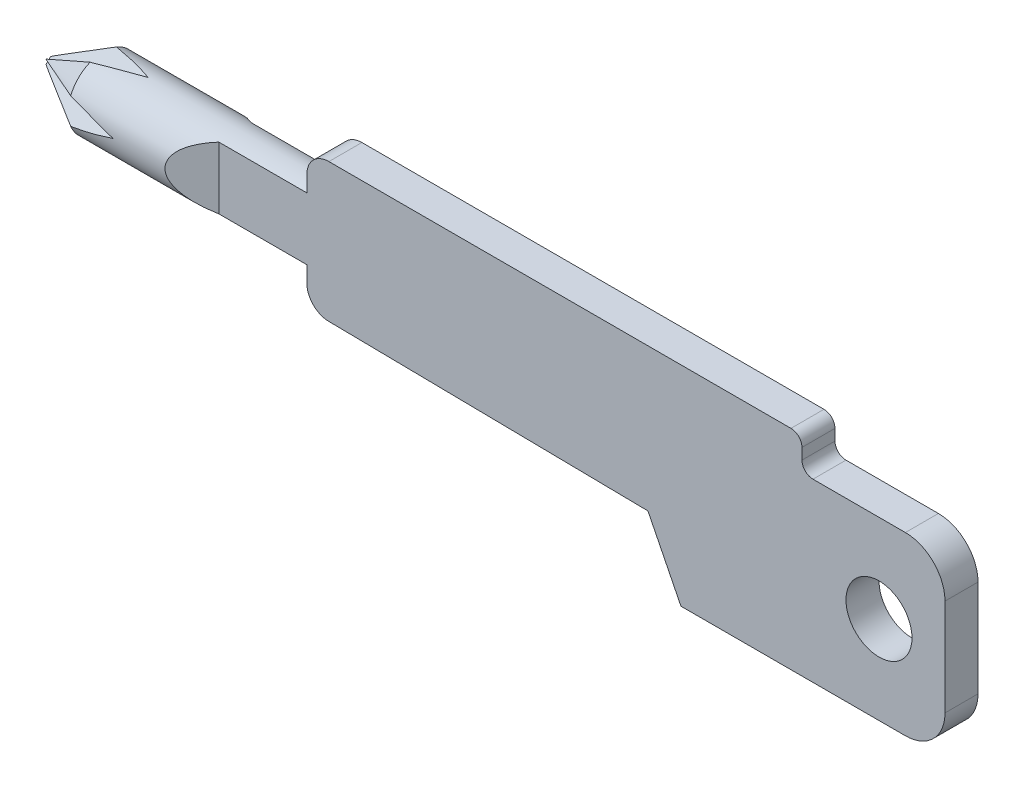
SolidWorks part; units mm, degrees
ref_plane "Front Plane" through (0, 0, 0) normal (0, 0, 1) x (1, 0, 0)
ref_plane "Top Plane" through (0, 0, 0) normal (0, 1, 0) x (1, 0, 0)
ref_plane "Right Plane" through (0, 0, 0) normal (1, 0, 0) x (0, 0, -1)
sketch "Sketch1" plane through (0, 0, 0) normal (0, 0, 1) x (1, 0, 0)
  line L2 (1, 9.5) -> (22, 9.5)
  line L3 (22.5, 9) -> (22.5, 8.5)
  line L4 (23, 8) -> (29, 8)
  line L5 (29, 8) -> (29, 0)
  line L6 (29, 0) -> (17, 0)
  line L21 (17, 0) -> (15.5, 3)
  line L22 (15.5, 3) -> (1, 3.2071)
  line L25 (0, 6.3536) -> (0, 8.5)
  line L26 (0, 6.3536) -> (0, 4.2071)
  arc A2 (23, 8) -> (22.5, 8.5) centre (23, 8.5) cw
  arc A3 (22.5, 9) -> (22, 9.5) centre (22, 9) ccw
  circle A6 centre (26, 4) radius 1.5
  arc A17 (0, 4.2071) -> (1, 3.2071) centre (1, 4.2071) ccw
  arc A18 (0, 8.5) -> (1, 9.5) centre (1, 8.5) cw
  point P3 (0, 0)
  point P15 (26, 8)
  point P18 (22.5, 8)
  point P22 (22.5, 9.5)
  point P24 (9.5435, 3.8604)
  point P27 (6.0812, 4.067)
  point P28 (0.2929, 3.5)
  point P29 (17.1415, 3)
  point P30 (0, 0)
  point P31 (0, 0)
  point P32 (13.8071, 3)
  point P33 (13.8626, 3)
  point P34 (14.3287, 3)
  point P35 (14.3287, 3)
  point P36 (0, 0)
  point P37 (0, 4.859)
  point P38 (16.1094, 3.2071)
  dimension "D12" = 1
  dimension "D13" = 0.5
  dimension "D7" = 12
  dimension "D8" = 4
  dimension "D2" = 3
  dimension "D9" = 6.5
  dimension "D14" = 7
  dimension "D3" = 1.5
  dimension "D4" = 26
  dimension "D5" = 8
  dimension "D6" = 6.5
  dimension "D10" = 6
extrude "Boss-Extrude1" add sketch "Sketch1" along normal mid plane 1.5
fillet "Fillet1" radius 1.8 2 edges at (29, 0, 0) (29, 8, 0)
sketch "Sketch2" plane through (0, 0, 0) normal (0, 0, 1) x (1, 0, 0)
  line L1 (0, 4.2071) -> (0, 8.5) construction
  line L2 (0, 7.9536) -> (0, 6.3536)
  line L3 (0, 6.3536) -> (-12.5, 6.3536)
  line L4 (-10, 7.9536) -> (0, 7.9536)
  line L5 (0, 4.2071) -> (0, 8.5) construction
  line L6 (-12.5, 6.3536) -> (-12.5, 6.5036)
  line L7 (-12.5, 6.5036) -> (-10, 7.9536)
  point P10 (0, 6.3536)
  dimension "D1" = 2.5
  dimension "D2" = 12.5
  dimension "D3" = 1.6
  dimension "D4" = 0.15
revolve "Revolve1" add sketch "Sketch2" angle 360 about L3
sketch "Sketch3" plane through (0, 0, 0) normal (0, 0, 1) x (1, 0, 0)
  line L0 (-12.5, 6.5036) -> (-10, 6.7036)
  line L1 (-10, 7.9536) -> (-10, 4.7536) construction
  line L2 (-10, 6.7036) -> (-8.5, 6.3536)
  line L3 (-8.5, 6.3536) -> (-10, 6.0036)
  line L4 (-10, 6.0036) -> (-12.5, 6.2036)
  line L5 (-12.5, 6.3536) -> (-7.5832, 6.3536) construction
  line L6 (-12.5, 6.5036) -> (-12.5, 6.2036) construction
  line L7 (0, 7.9536) -> (-10, 7.9536) construction
  line L8 (-12.5, 6.5036) -> (-12.5, 6.2036)
  dimension "D1" = 1.25
  dimension "D2" = 4
ref_plane "Plane2" through (0, 0, 1.75) normal (0, 0, 1) x (1, 0, 0)
sketch "Sketch10" plane through (-12.5, 0, 0) normal (-1, 0, 0) x (0, 0, 1)
  line L0 (0, 6.3536) -> (-3, 9.3536)
  line L1 (-3, 9.3536) -> (3, 9.3536)
  line L2 (3, 9.3536) -> (0, 6.3536)
  line L3 (0, 6.3536) -> (0, 9.6461) construction
  dimension "D1" = 3
  dimension "D2" = 90
extrude "Cut-Extrude4" cut sketch "Sketch10" against normal blind 5 draft 14
pattern_circular "CirPattern3" count 4 over 360 about axis through (0, 6.3536, 0) along (1, 0, 0) of "Cut-Extrude4"
sketch "Sketch12" plane through (0, 0, 0) normal (1, 0, 0) x (0, 0, -1)
  line L0 (0.75, 4.9402) -> (0.75, 7.7669) construction
  line L1 (-0.75, 4.9402) -> (-0.75, 7.7669) construction
  line L2 (0.75, 4.9402) -> (0.75, 7.7669)
  line L3 (-0.75, 4.9402) -> (-0.75, 7.7669)
  arc A0 (0.75, 4.9402) -> (0.75, 7.7669) centre (0, 6.3536) ccw construction
  arc A1 (-0.75, 7.7669) -> (-0.75, 4.9402) centre (0, 6.3536) ccw construction
  arc A2 (0.75, 4.9402) -> (0.75, 7.7669) centre (0, 6.3536) ccw
  arc A3 (-0.75, 7.7669) -> (-0.75, 4.9402) centre (0, 6.3536) ccw
extrude "Cut-Extrude6" cut sketch "Sketch12" against normal blind 4
ref_plane "Plane3" through (0, 7.9536, 0) normal (0, 1, 0) x (1, 0, 0)
sketch "Sketch13" plane through (0, 7.9536, 0) normal (0, 1, 0) x (1, 0, 0)
  line L0 (-4, -0.75) -> (-4, -1.6)
  line L1 (-4, -1.6) -> (-5.6, -1.6)
  line L2 (-7.9623, -1.6) -> (-4, -1.6) construction
  line L3 (-5.6, -1.6) -> (-4, -0.75)
  line L4 (0, 0) -> (-6.5481, 0) construction
  line L5 (-4, 0.75) -> (-4, 1.6)
  line L6 (-4, 1.6) -> (-5.6, 1.6)
  line L7 (-5.6, 1.6) -> (-4, 0.75)
  dimension "D1" = 1.6
extrude "Cut-Extrude7" cut sketch "Sketch13" against normal through all
